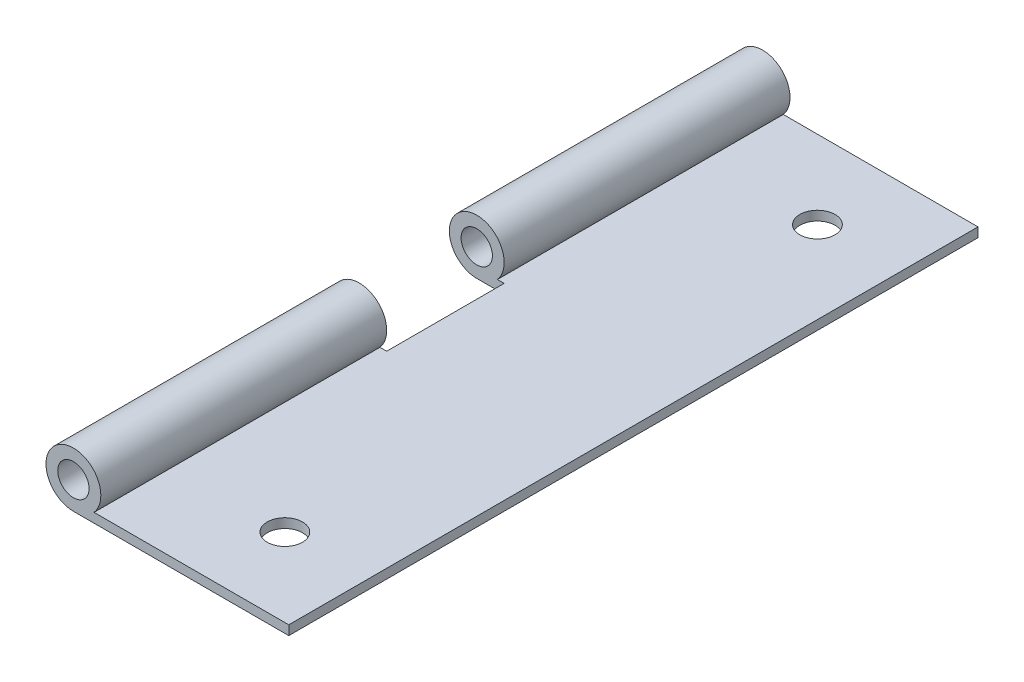
SolidWorks part; units mm, degrees
ref_plane "Front Plane" through (0, 0, 0) normal (0, 0, 1) x (1, 0, 0)
ref_plane "Top Plane" through (0, 0, 0) normal (0, 1, 0) x (1, 0, 0)
ref_plane "Right Plane" through (0, 0, 0) normal (1, 0, 0) x (0, 0, -1)
sketch "Sketch1" plane through (0, 0, 0) normal (0, 1, 0) x (1, 0, 0)
  line L1 (-12, -44) -> (12, -44)
  line L2 (-12, -44) -> (-12, 44)
  line L3 (-12, 44) -> (12, 44)
  line L4 (12, -44) -> (12, 44)
  line L5 (-12, -44) -> (12, 44) construction
  line L6 (-12, 44) -> (12, -44) construction
  point P0 (0, 0)
  dimension "D1" = 88
  dimension "D2" = 24
extrude "Boss-Extrude1" add sketch "Sketch1" along normal blind 1.2
sketch "Sketch2" plane through (0, 0, 0) normal (0, 0, 1) x (1, 0, 0)
  line L0 (-12, 0) -> (12, 0) construction
  line L2 (12, 1.2) -> (12, 0) construction
  line L3 (-12, 0) -> (-15.5, 0)
  line L4 (-12, 1.2) -> (-12.8618, 1.2)
  line L5 (-12, 1.2) -> (-12, 0)
  arc A0 (-12.8618, 1.2) -> (-15.5, 0) centre (-15.5, 3.5) ccw
  circle A1 centre (-15.5, 3.5) radius 2
  point P5 (-19, 3.5)
  dimension "D2" = 7
  dimension "D3" = 4
  dimension "D1" = 27.5
extrude "Boss-Extrude2" add sketch "Sketch2" along normal up to surface (36.5 mm away) from offset 7.5 up to face at (0, 0.6, 44)
mirror "Mirror4" about plane through (0, 0, 0) normal (0, 0, 1) of bodies 104
sketch "Sketch4" plane through (0, 1.2, 0) normal (0, 1, 0) x (1, 0, 0)
  line L0 (1.5, -44) -> (1.5, 44) construction
  line L1 (-12.8618, -44) -> (12, -44) construction
  line L2 (12, 44) -> (-12.8618, 44) construction
  line L3 (0, 0) -> (12, 0) construction
  line L4 (12, -44) -> (12, 44) construction
  circle A0 centre (1.5, 34) radius 2.25
  circle A1 centre (1.5, -34) radius 2.25
  point P6 (-19, -7.5)
  point P15 (-15.5, -7.5)
  dimension "D2" = 4.5
  dimension "D3" = 34
  dimension "D1" = 17
extrude "Cut-Extrude2" cut sketch "Sketch4" against normal through all
